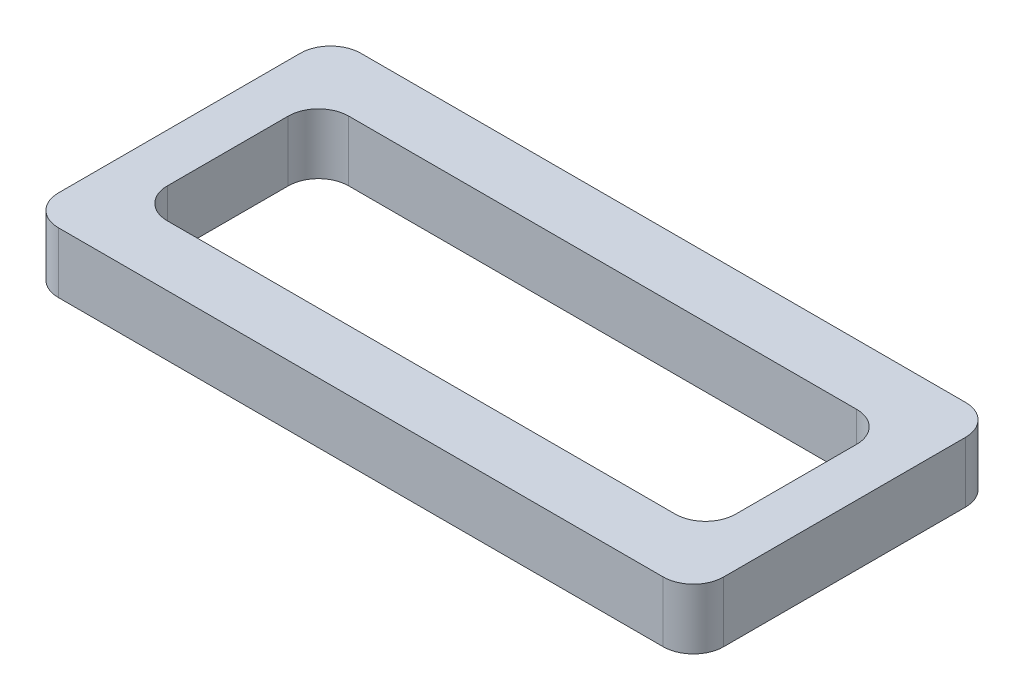
SolidWorks part; units mm, degrees
material "Acrylic (Medium-high impact)"
ref_plane "Front Plane" through (0, 0, 0) normal (0, 0, 1) x (1, 0, 0)
ref_plane "Top Plane" through (0, 0, 0) normal (0, 1, 0) x (1, 0, 0)
ref_plane "Right Plane" through (0, 0, 0) normal (1, 0, 0) x (0, 0, -1)
sketch "Sketch1" plane through (0, 0, 0) normal (0, 1, 0) x (1, 0, 0)
  line L0 (0, 130.8443) -> (0, -85.764) construction
  line L11 (-55, -25) -> (-55, 25)
  line L12 (-55, 25) -> (55, 25)
  line L13 (55, 25) -> (55, -25)
  line L18 (47, -15) -> (-47, -15)
  line L19 (47, -15) -> (47, 15)
  line L20 (47, 15) -> (-47, 15)
  line L21 (-47, -15) -> (-47, 15)
  line L22 (47, -15) -> (-47, 15) construction
  line L23 (47, 15) -> (-47, -15) construction
  line L27 (-55, -25) -> (55, -25)
  point P20 (0, 25)
  point P21 (0, 0)
  dimension "D3" = 110
  dimension "D4" = 50
  dimension "D8" = 94
  dimension "D9" = 10
  dimension "D10" = 30
extrude "Boss-Extrude1" add sketch "Sketch1" along normal blind 10 contours L12 L13 L11
fillet "Fillet1" radius 5 8 edges at (47, 5, 15) (47, 5, -15) (-47, 5, 15) (-47, 5, -15) (-55, 5, -25) (55, 5, -25) (55, 5, 25) (-55, 5, 25)
